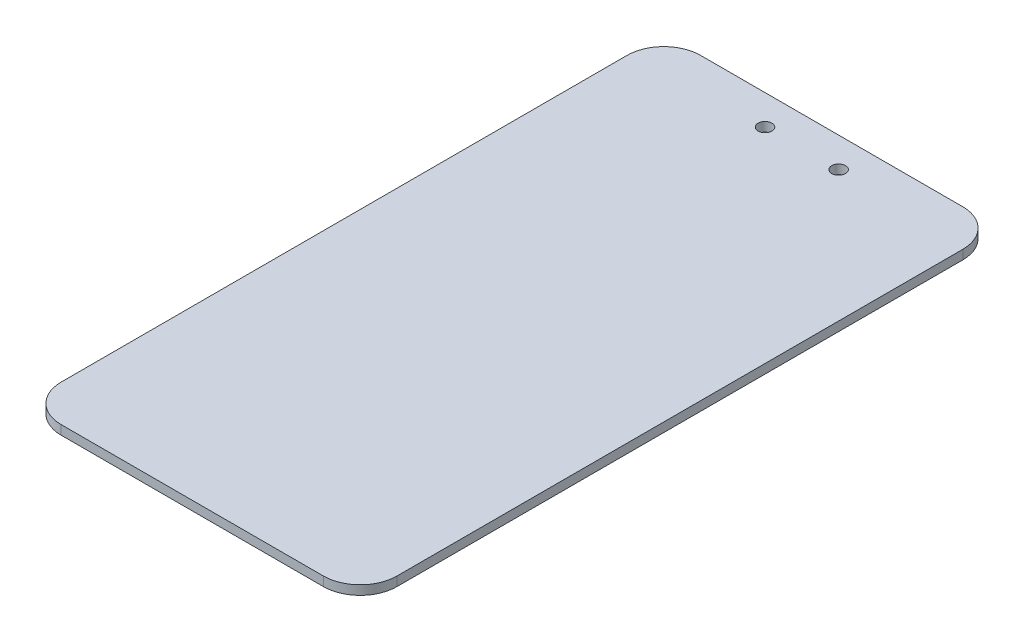
SolidWorks part; units mm, degrees
ref_plane "Front Plane" through (0, 0, 0) normal (0, 0, 1) x (1, 0, 0)
ref_plane "Top Plane" through (0, 0, 0) normal (0, 1, 0) x (1, 0, 0)
ref_plane "Right Plane" through (0, 0, 0) normal (1, 0, 0) x (0, 0, -1)
sketch "Sketch1" plane through (0, 0, 0) normal (0, 1, 0) x (1, 0, 0)
  line L0 (0, 69.5) -> (73, 69.5) construction
  line L1 (8, 0) -> (65, 0)
  line L2 (0, 8) -> (0, 131)
  line L3 (8, 139) -> (65, 139)
  line L4 (73, 8) -> (73, 131)
  line L5 (36.5, 139) -> (36.5, 0) construction
  circle A0 centre (44.5, 132.5) radius 1.5
  circle A1 centre (28.5, 132.5) radius 1.5
  arc A2 (8, 0) -> (0, 8) centre (8, 8) cw
  arc A3 (65, 0) -> (73, 8) centre (65, 8) ccw
  arc A4 (65, 139) -> (73, 131) centre (65, 131) cw
  arc A5 (0, 131) -> (8, 139) centre (8, 131) cw
  point P15 (0, 0)
  point P18 (73, 0)
  point P23 (0, 139)
  dimension "D3" = 3
  dimension "D6" = 8
  dimension "D1" = 73
  dimension "D2" = 139
  dimension "D4" = 6.5
  dimension "D5" = 8
extrude "Boss-Extrude1" add sketch "Sketch1" along normal blind 2
